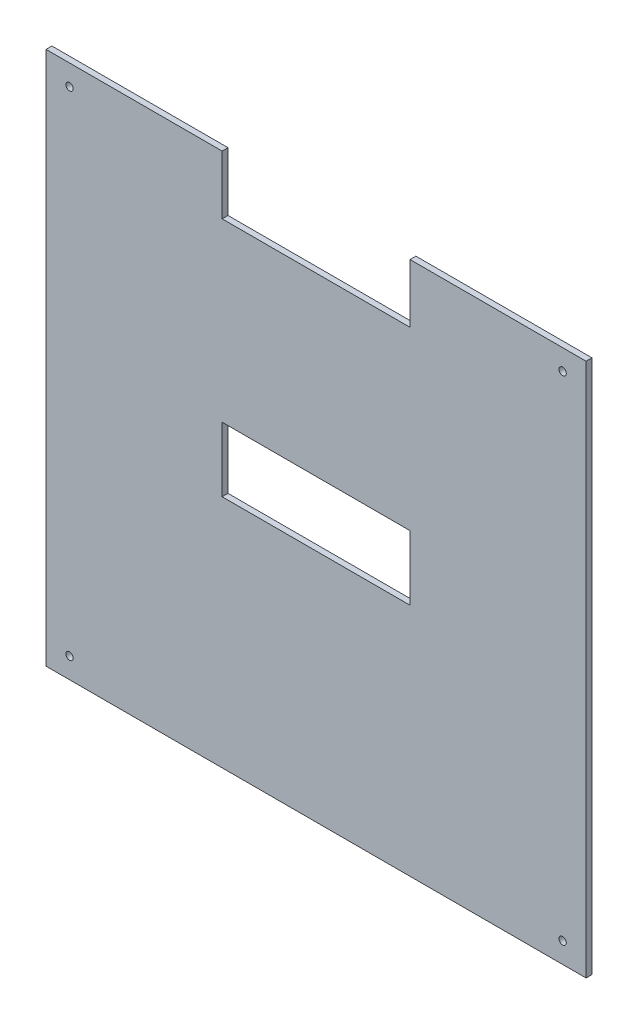
SolidWorks part; units mm, degrees
ref_plane "正面" through (0, 0, 0) normal (0, 0, 1) x (1, 0, 0)
ref_plane "平面" through (0, 0, 0) normal (0, 1, 0) x (1, 0, 0)
ref_plane "右側面" through (0, 0, 0) normal (1, 0, 0) x (0, 0, -1)
sketch "ｽｹｯﾁ1" plane through (0, 0, 0) normal (0, 0, 1) x (1, 0, 0)
  line L1 (0, 0) -> (184, 0)
  line L2 (0, 0) -> (0, 182)
  line L3 (0, 182) -> (184, 182)
  line L4 (184, 0) -> (184, 182)
  dimension "D1" = 182
  dimension "D2" = 184
extrude "ﾎﾞｽ - 押し出し1" add sketch "ｽｹｯﾁ1" along normal blind 2
hole_wizard "M3x0.5 ねじ穴1" positions "ｽｹｯﾁ2" profile "ｽｹｯﾁ3" tap size "M3x0.5" standard "JIS" end condition through all
sketch "ｽｹｯﾁ2" plane through (0, 0, 2) normal (0, 0, 1) x (1, 0, 0)
  line L0 (0, 182) -> (0, 0) construction
  line L2 (0, 0) -> (184, 0) construction
  line L3 (184, 0) -> (184, 182) construction
  line L4 (184, 182) -> (0, 182) construction
  point P0 (8, 175)
  point P2 (8, 7)
  point P4 (176, 7)
  point P6 (176, 175)
  dimension "D1" = 8
  dimension "D2" = 7
  dimension "D3" = 7
  dimension "D4" = 8
  dimension "D5" = 7
  dimension "D6" = 8
  dimension "D7" = 7
  dimension "D8" = 8
  dimension "D9" = 168
  dimension "D10" = 168
sketch "ｽｹｯﾁ3" plane through (8, 175, 2) normal (1, 0, 0) x (0, -1, 0)
  line L0 (0, 0) -> (0, 2)
  line L1 (0, 2) -> (1.25, 2)
  line L2 (1.25, 2) -> (1.25, 0)
  line L5 (1.25, 0) -> (0, 0)
  line L11 (0, -6.35) -> (0, 107.95) construction
  dimension "次ｻｰﾌｪｽまでのねじ下穴ﾄﾞﾘﾙ直径" = 2.5
  dimension "次ｻｰﾌｪｽまでのねじ下穴ﾄﾞﾘﾙの深さ" = 2
cosmetic thread "穴のねじ山1" parameters "D2"=3
cosmetic thread "穴のねじ山2" parameters "D2"=3
cosmetic thread "穴のねじ山3" parameters "D2"=3
cosmetic thread "穴のねじ山4" parameters "D2"=3
ref_plane "平面1" through (92, 0, 0) normal (1, 0, 0) x (0, 0, -1)
ref_plane "平面2" through (0, 91, 0) normal (0, 1, 0) x (1, 0, 0)
sketch "ｽｹｯﾁ4" plane through (0, 0, 0) normal (0, 0, -1) x (-1, 0, 0)
  line L0 (-184, 182) -> (0, 182) construction
  line L1 (-60, 182) -> (-124, 182)
  line L2 (-60, 182) -> (-60, 162)
  line L3 (-60, 162) -> (-124, 162)
  line L4 (-124, 182) -> (-124, 162)
  line L5 (0, 1.1) -> (0, -1.1) construction
  line L6 (-184, 0) -> (-184, 182) construction
  dimension "D1" = 60
  dimension "D2" = 20
  dimension "D3" = 60
extrude "ｶｯﾄ - 押し出し1" cut sketch "ｽｹｯﾁ4" against normal through all
sketch "ｽｹｯﾁ6" plane through (0, 0, 0) normal (0, 0, -1) x (-1, 0, 0)
  line L0 (-184, 0) -> (-184, 182) construction
  line L1 (-124, 102) -> (-60, 102)
  line L2 (-124, 102) -> (-124, 80)
  line L3 (-124, 80) -> (-60, 80)
  line L4 (-60, 102) -> (-60, 80)
  line L5 (0, 1.1) -> (0, -1.1) construction
  line L6 (1.1, 0) -> (-1.1, 0) construction
  line L7 (-184, 182) -> (-124, 182) construction
  dimension "D1" = 60
  dimension "D2" = 60
  dimension "D3" = 80
  dimension "D4" = 80
extrude "ｶｯﾄ - 押し出し2" cut sketch "ｽｹｯﾁ6" against normal blind 10
